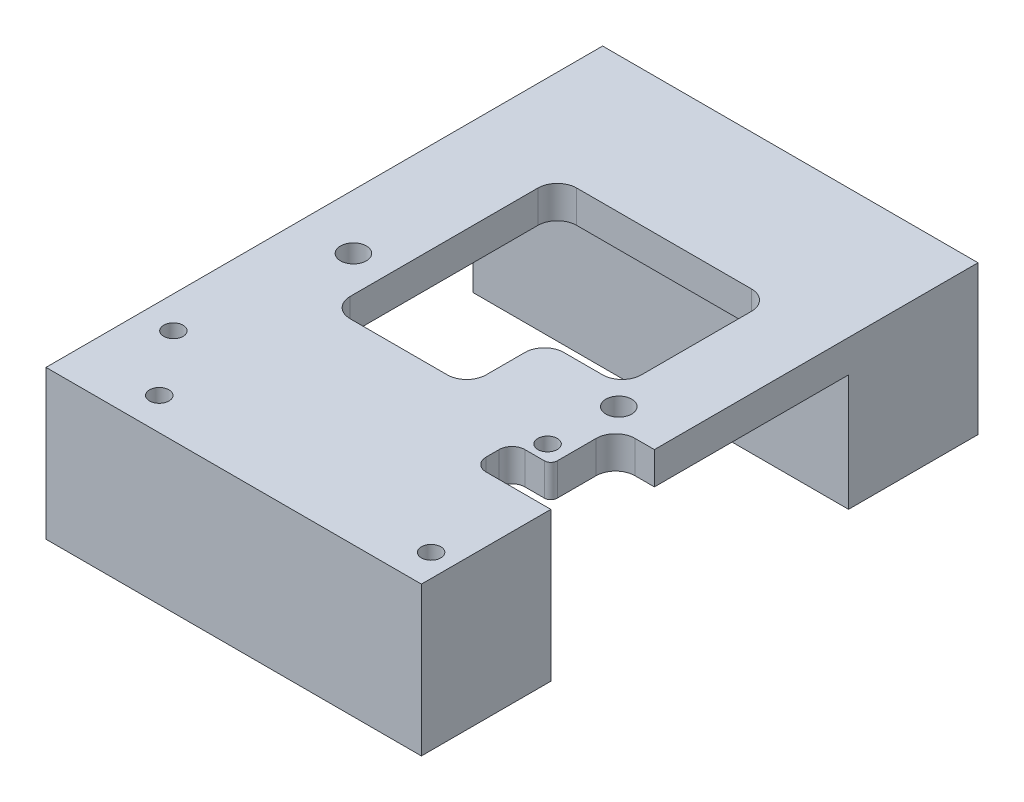
SolidWorks part; units mm, degrees
ref_plane "Front Plane" through (0, 0, 0) normal (0, 0, 1) x (1, 0, 0)
ref_plane "Top Plane" through (0, 0, 0) normal (0, 1, 0) x (1, 0, 0)
ref_plane "Right Plane" through (0, 0, 0) normal (1, 0, 0) x (0, 0, -1)
sketch "Sketch1" plane through (0, 0, 0) normal (0, 1, 0) x (1, 0, 0)
  line L0 (29, 0) -> (-29, 0) construction
  line L1 (0, -43) -> (0, 43) construction
  line L2 (-29, -43) -> (-29, 43)
  line L3 (-29, 43) -> (29, 43)
  line L4 (29, 43) -> (29, -43)
  line L5 (-29, -43) -> (29, -43)
  point P4 (0, 0)
  point P8 (0, 0)
  dimension "D1" = 58
  dimension "D2" = 43
extrude "Boss-Extrude1" add sketch "Sketch1" along normal blind 23
sketch "Sketch2" plane through (0, 0, 0) normal (0, 1, 0) x (1, 0, 0)
  line L0 (29, -43) -> (29, -23) construction
  line L1 (29, -43) -> (29, 43) construction
  line L2 (29, -23) -> (17, -23)
  line L3 (17, -23) -> (17, -17)
  line L4 (17, -17) -> (23, -17)
  line L5 (23, -17) -> (23, -7)
  line L6 (23, -7) -> (29, -7)
  line L7 (29, -7) -> (29, -23)
  dimension "D1" = 12
  dimension "D2" = 20
  dimension "D3" = 6
  dimension "D4" = 6
  dimension "D5" = 10
extrude "Cut-Extrude1" cut sketch "Sketch2" along normal blind 23
sketch "Sketch3" plane through (0, 0, 0) normal (0, 1, 0) x (1, 0, 0)
  line L0 (-29, -43) -> (-15, -43) construction
  line L1 (-29, -43) -> (29, -43) construction
  line L2 (-15, -43) -> (-15, -13) construction
  line L3 (-15, -13) -> (-15, 22)
  line L4 (-15, 22) -> (18, 22)
  line L5 (-15, -13) -> (6, -13)
  line L6 (18, 22) -> (18, -1)
  line L7 (6, -13) -> (6, -1)
  line L8 (6, -1) -> (18, -1)
  dimension "D1" = 14
  dimension "D2" = 30
  dimension "D3" = 35
  dimension "D4" = 33
  dimension "D5" = 21
  dimension "D6" = 23
extrude "Cut-Extrude2" cut sketch "Sketch3" along normal blind 23
fillet "Fillet1" radius 3 1 edges at (23, 11.5, 7)
fillet "Fillet2" radius 2 1 edges at (17, 11.5, 17)
fillet "Fillet3" radius 2 1 edges at (17, 11.5, 23)
fillet "Fillet4" radius 1 1 edges at (23, 11.5, 17)
fillet "Fillet5" radius 3 1 edges at (-15, 11.5, 13)
fillet "Fillet6" radius 3 1 edges at (6, 11.5, 13)
fillet "Fillet7" radius 3 1 edges at (-15, 11.5, -22)
fillet "Fillet8" radius 3 1 edges at (18, 11.5, -22)
fillet "Fillet9" radius 3 1 edges at (18, 11.5, 1)
fillet "Fillet10" radius 3 1 edges at (6, 11.5, 1)
sketch "Sketch4" plane through (0, 0, 0) normal (1, 0, 0) x (0, 0, -1)
  line L0 (-23, 0) -> (-23, 18)
  line L1 (-23, 23) -> (-23, 0) construction
  line L2 (-43, 23) -> (-23, 23) construction
  line L3 (-23, 0) -> (23, 0)
  line L4 (-7, 0) -> (43, 0) construction
  line L5 (23, 0) -> (23, 18)
  line L6 (23, 18) -> (-23, 18)
  dimension "D1" = 5
  dimension "D2" = 20
extrude "Cut-Extrude3" cut sketch "Sketch4" against normal through all both and the other way through all
sketch "Sketch5" plane through (0, 0, 0) normal (0, 1, 0) x (1, 0, 0)
  line L0 (20.5, -43) -> (20.5, -4) construction
  line L1 (-29, -43) -> (29, -43) construction
  line L2 (20.5, -4) -> (-20.5, -4) construction
  line L3 (23, -14.5) -> (20, -14.5) construction
  line L5 (23, -10) -> (23, -16) construction
  line L7 (20, -14.5) -> (20, -43) construction
  line L8 (29, -38) -> (25.5, -38) construction
  line L9 (29, -43) -> (29, -23) construction
  line L10 (25.5, -38) -> (-16.5, -38) construction
  line L11 (-29, -43) -> (-25, -43) construction
  circle A0 centre (20.5, -4) radius 2
  circle A1 centre (-20.5, -4) radius 2
  circle A3 centre (20, -14.5) radius 1.5
  circle A4 centre (-16.5, -38) radius 1.5
  circle A5 centre (25.5, -38) radius 1.5
  circle A7 centre (-24.0516, -28.2591) radius 1.5
  dimension "D2" = 4
  dimension "D5" = 4
  dimension "D7" = 28.5
  dimension "D8" = 3
  dimension "D12" = 3
  dimension "D13" = 3
  dimension "D15" = 3
  dimension "D1" = 8.5
  dimension "D3" = 39
  dimension "D4" = 41
  dimension "D6" = 3
  dimension "D9" = 3.5
  dimension "D10" = 42
  dimension "D11" = 5
  dimension "D14" = 4
extrude "Cut-Extrude4" cut sketch "Sketch5" against normal through all and the other way through all
sketch "Sketch6" plane through (-29, 0, 0) normal (-1, 0, 0) x (0, 0, 1)
  line L0 (43, 23) -> (43, 0) construction
  line L1 (23, 0) -> (43, 0) construction
  line L2 (23, 18) -> (23, 0) construction
  circle A0 centre (40, 3) radius 1.5
  circle A1 centre (26, 18) radius 1.5
  dimension "D3" = 3
  dimension "D6" = 3
  dimension "D1" = 3
  dimension "D2" = 3
  dimension "D4" = 3
  dimension "D5" = 18
extrude "Cut-Extrude11" cut sketch "Sketch6" against normal blind 10
sketch "Sketch7" plane through (0, 0, -43) normal (0, 0, -1) x (-1, 0, 0)
  line L0 (-29, 0) -> (29, 0) construction
  line L1 (-29, 23) -> (-29, 0) construction
  line L2 (-29, 23) -> (29, 23) construction
  circle A0 centre (-19.5, 4.5) radius 1.5
  circle A1 centre (-19.5, 18.5) radius 1.5
  dimension "D1" = 3
  dimension "D5" = 3
  dimension "D2" = 4.5
  dimension "D3" = 9.5
  dimension "D4" = 4.5
  dimension "D6" = 9.5
extrude "Cut-Extrude12" cut sketch "Sketch7" against normal blind 10
